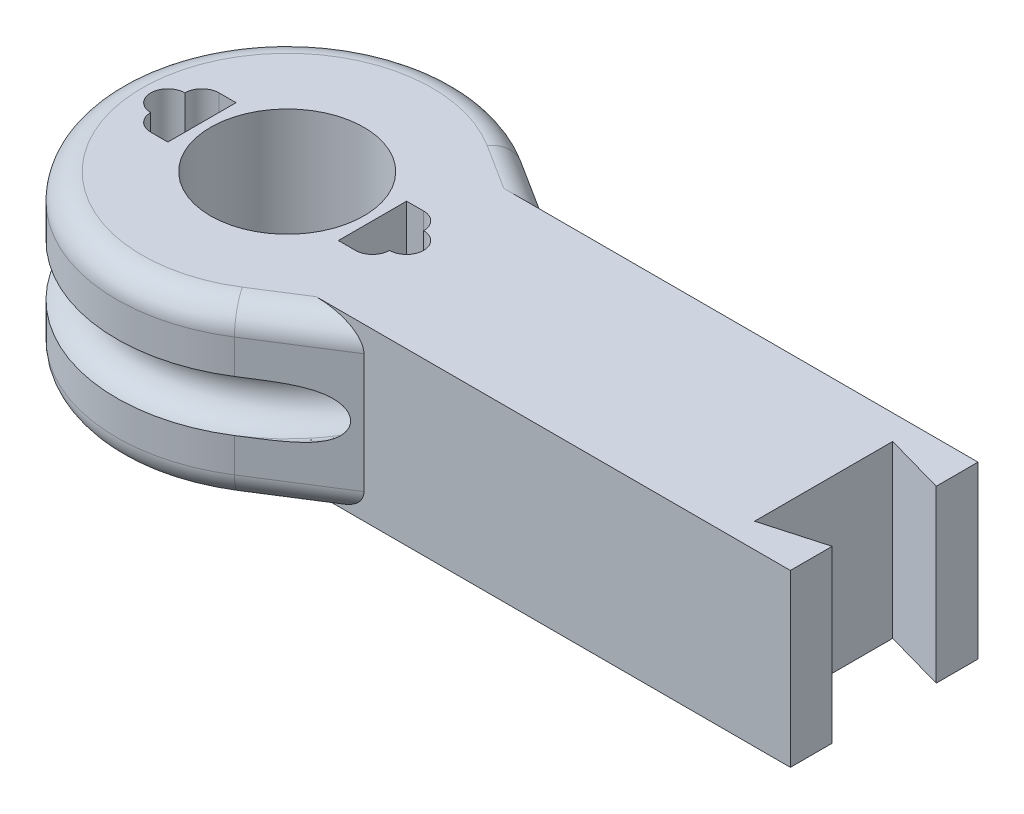
SolidWorks part; units mm, degrees
ref_plane "Front Plane" through (0, 0, 0) normal (0, 0, 1) x (1, 0, 0)
ref_plane "Top Plane" through (0, 0, 0) normal (0, 1, 0) x (1, 0, 0)
ref_plane "Right Plane" through (0, 0, 0) normal (1, 0, 0) x (0, 0, -1)
sketch "Sketch1" plane through (0, 0, 0) normal (0, 1, 0) x (1, 0, 0)
  line L0 (-12.4221, 0) -> (31.45, 0) construction
  line L1 (0, 8.1775) -> (0, -7.8417) construction
  line L2 (10, 5.5) -> (5.3551, 8.4453)
  line L3 (10, -5.5) -> (35, -5.5)
  line L5 (10, 5.5) -> (35, 5.5)
  line L6 (35, -5.5) -> (35, -3.05)
  line L7 (10, -5.5) -> (35, 5.5) construction
  line L8 (10, 5.5) -> (35, -5.5) construction
  line L9 (10, -5.5) -> (5.3551, -8.4453)
  line L10 (10, 5.5) -> (10, -5.5) construction
  line L11 (5, 2) -> (6, 2)
  line L12 (-5, -2) -> (-6, -2)
  line L13 (-5, -2) -> (-5, 2)
  line L14 (-5, 2) -> (-6, 2)
  line L15 (-7, -1) -> (-7, 1)
  line L18 (7, -1) -> (7, 1)
  line L19 (5, -2) -> (6, -2)
  line L20 (5, -2) -> (5, 2)
  line L21 (35, 3.05) -> (31.45, 4.05)
  line L23 (31.45, -4.05) -> (31.45, 4.05)
  line L26 (31.45, -4.05) -> (31.5208, -3.9692) construction
  line L27 (31.45, 4.05) -> (31.5208, 3.9692) construction
  line L28 (35, -3.05) -> (31.45, -4.05)
  line L30 (35, 3.05) -> (35, 5.5)
  arc A0 (5.3551, 8.4453) -> (5.3551, -8.4453) centre (0, 0) ccw
  circle A1 centre (0, 0) radius 4.5
  arc A2 (-6, -2) -> (-7, -1) centre (-6, -1) cw
  arc A3 (-6, 2) -> (-7, 1) centre (-6, 1) ccw
  circle A4 centre (-7, 0) radius 1
  circle A5 centre (7, 0) radius 1
  arc A6 (6, 2) -> (7, 1) centre (6, 1) cw
  arc A7 (6, -2) -> (7, -1) centre (6, -1) ccw
  point P7 (22.5, 0)
  point P12 (-6, 0)
  point P19 (-5, 0)
  point P20 (-4.5, 0)
  point P39 (35, 0)
  point P44 (35, 3.05)
  point P45 (35, 4.05)
  point P48 (35, -3.05)
  dimension "D1" = 20
  dimension "D4" = 9
  dimension "D8" = 1
  dimension "D9" = 2
  dimension "D2" = 25
  dimension "D3" = 11
  dimension "D5" = 4
  dimension "D7" = 0.5
  dimension "D12" = 1
extrude "Boss-Extrude2" add sketch "Sketch1" along normal blind 10 contours L15 A4 | L15 A4 | A4 A2 L12 L13 L14 A3 | A1 | L19 A7 A5 A6 L11 L20 | A5 L18 | L3 L6 L28 L23 L21 L30 L5 L2 A0 L9
sketch "Sketch4" plane through (-6.6668, 16.5353, 0) normal (0, 0, 1) x (0, 1, 0)
  line L3 (-6.5353, 3.3332) -> (-16.5353, 3.3332) construction
  line L8 (-16.5353, -6.6668) -> (-4.9826, -6.6668) construction
  line L13 (-12.596, 2.2725) -> (-10.6227, 4.2458) construction
  line L14 (-12.4479, 4.2458) -> (-10.4746, 2.2725) construction
  arc A0 (-13.0353, 3.3332) -> (-10.0353, 3.3332) centre (-11.5353, 3.3332) ccw
  ellipse E0 centre (-11.5353, 3.3332) end of major axis (-10.0353, 3.3332) minor radius 1.15 (-10.0353, 3.3332) -> (-13.0353, 3.3332) ccw
  point P0 (-11.5353, 3.3332)
  point P1 (-11.5353, 3.3332)
  point P22 (-11.5353, 3.3332)
  dimension "D3" = 1.15
revolve "Cut-Revolve3" cut sketch "Sketch4" angle 360 about L8
fillet "Fillet2" radius 1.5 6 edges at (7.6775, 10, -6.9726) (7.6775, 0, -6.9726) (7.6775, 0, 6.9726) (7.6775, 10, 6.9726) (-10, 0, 0) (-10, 10, 0)
